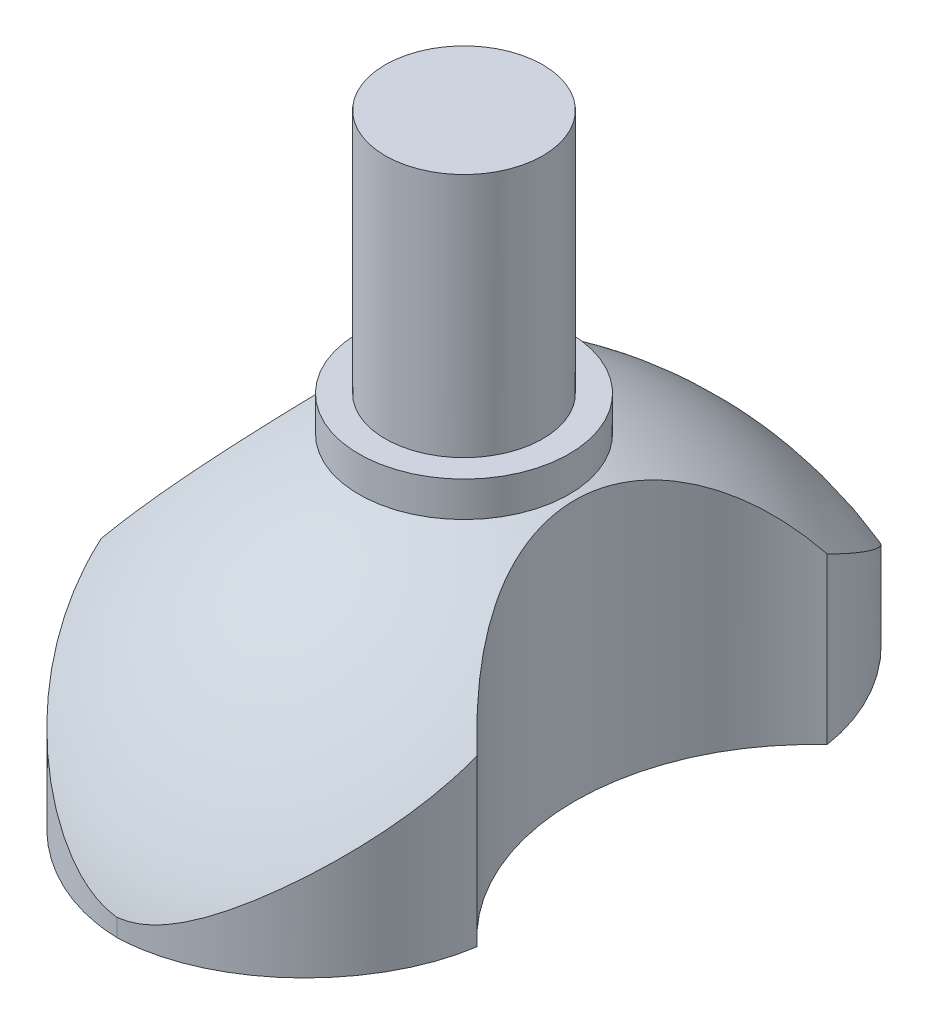
SolidWorks part; units mm, degrees
ref_plane "Front Plane" through (0, 0, 0) normal (0, 0, 1) x (1, 0, 0)
ref_plane "Top Plane" through (0, 0, 0) normal (0, 1, 0) x (1, 0, 0)
ref_plane "Right Plane" through (0, 0, 0) normal (1, 0, 0) x (0, 0, -1)
sketch "Sketch1" plane through (0, 0, 0) normal (0, 1, 0) x (1, 0, 0)
  circle A0 centre (0, 0) radius 5
  circle A1 centre (0, 0) radius 3
  dimension "D1" = 6
  dimension "D2" = 10
extrude "Boss-Extrude2" add sketch "Sketch1" along normal mid plane 35
sketch "Sketch4" plane through (0, 17.5, 0) normal (0, 1, 0) x (1, 0, 0)
  line L0 (3, 0) -> (21, 0)
  circle A0 centre (0, 0) radius 3 construction
  dimension "D1" = 18
extrude "Extrude-Thin1" add sketch "Sketch4" against normal blind 35 thin thin type mid plane wall 1
pattern_circular "CirPattern1" count 9 over 360 about axis through (0, 0, 0) along (0, 1, 0) of "Extrude-Thin1"
ref_plane "Plane1" through (0, -17.5, 0) normal (0, -1, 0) x (-1, 0, 0)
sketch "Sketch5" plane through (0, -17.5, 0) normal (0, -1, 0) x (-1, 0, 0)
  circle A0 centre (0, 0) radius 3
extrude "Boss-Extrude3" add sketch "Sketch5" against normal blind 15
sketch "Sketch6" plane through (0, -17.5, 0) normal (0, -1, 0) x (-1, 0, 0)
  circle A0 centre (0, 0) radius 3.5
  circle A1 centre (0, 0) radius 5
  circle A2 centre (0, 0) radius 1.5
  dimension "D1" = 1.5
  dimension "D2" = 10
  dimension "D3" = 2
extrude "Cut-Extrude1" cut sketch "Sketch6" against normal blind 6 contours A0 A2
sketch "Sketch15" plane through (0, -17.5, 0) normal (0, -1, 0) x (1, 0, 0)
  circle A0 centre (0, 0) radius 1.5
extrude "Cut-Extrude2" cut sketch "Sketch15" against normal blind 2
sketch "Sketch17" plane through (0, -17.5, 0) normal (0, -1, 0) x (1, 0, 0)
  line L0 (21, -0.5) -> (21, 0.5) construction
  circle A0 centre (18.5, 0) radius 2.5
  dimension "D1" = 5
  dimension "D2" = 2.5
extrude "Boss-Extrude4" add sketch "Sketch17" against normal blind 3
sketch "Sketch18" plane through (0, -17.5, 0) normal (0, -1, 0) x (1, 0, 0)
  circle A0 centre (18.5, 0) radius 2
  dimension "D1" = 4
extrude "Cut-Extrude3" cut sketch "Sketch18" against normal blind 2
sketch "Sketch19" plane through (0, 17.5, 0) normal (0, 1, 0) x (1, 0, 0)
  circle A0 centre (0, 0) radius 4
  circle A1 centre (0, 0) radius 3 construction
  dimension "D1" = 1
extrude "Cut-Extrude4" cut sketch "Sketch19" against normal up to surface (20 mm away) up to face at (0, -2.5, -3)
sketch "Sketch20" plane through (0, -17.5, 0) normal (0, -1, 0) x (-1, 0, 0)
  line L1 (22.8386, 22.8623) -> (-22.8386, 22.8623)
  line L2 (22.8386, 22.8623) -> (22.8386, -22.8623)
  line L3 (22.8386, -22.8623) -> (-22.8386, -22.8623)
  line L4 (-22.8386, 22.8623) -> (-22.8386, -22.8623)
  line L5 (22.8386, 22.8623) -> (-22.8386, -22.8623) construction
  line L6 (22.8386, -22.8623) -> (-22.8386, 22.8623) construction
  point P0 (0, 0)
extrude "Cut-Extrude5" cut sketch "Sketch20" against normal blind 8
sketch "Sketch21" plane through (0, -9.5, 0) normal (0, -1, 0) x (1, 0, 0)
  circle A0 centre (0, 0) radius 3
  dimension "D1" = 6
extrude "Boss-Extrude5" add sketch "Sketch21" along normal blind 1
sketch "Sketch22" plane through (0, 0, 0) normal (0, 0, 1) x (1, 0, 0)
  line L0 (0, 0) -> (0, -37.0893) construction
sketch "Sketch23" plane through (0, 0, 0) normal (1, 0, 0) x (0, 0, -1)
  line L0 (-8.7928, -17.5) -> (7.1377, -17.5) construction
  line L1 (-13.1155, -9.5) -> (-2.8148, -9.5) construction
  line L2 (-55, -17.5) -> (55, -17.5) construction
  line L3 (-3, -10.5) -> (-2, -10.5)
  line L4 (-3, -10.5) -> (3, -10.5) construction
  line L5 (-9.9121, -17.5) -> (-8.9121, -17.5)
  line L6 (0, -11.1307) -> (0, -16.3839) construction
  line L7 (0, 0) -> (0, -37.0893) construction
  line L8 (-8.9121, -17.5) -> (0, -17.5)
  line L9 (0, -17.5) -> (0, -10.5)
  line L10 (0, -10.5) -> (-2, -10.5)
  arc A0 (-3, -10.5) -> (-9.9121, -17.5) centre (0.7568, -21.1223) ccw
  dimension "D1" = 8
  dimension "D2" = 1
  dimension "D3" = 1
revolve "Revolve1" add sketch "Sketch23" angle 360 about L6
sketch "Sketch24" plane through (0, -17.5, 0) normal (0, -1, 0) x (1, 0, 0)
  circle A2 centre (0, 0) radius 9.9121
  circle A3 centre (0, 0) radius 9.9121
  dimension "D1" = 0
extrude "Boss-Extrude6" add sketch "Sketch24" along normal blind 0.5
sketch "Sketch25" plane through (0, -18, 0) normal (0, -1, 0) x (1, 0, 0)
  line L0 (-1.1163, 9.8491) -> (1.1163, -9.8491) construction
  circle A0 centre (0, 0) radius 9.9121 construction
  circle A1 centre (-0.5667, 5) radius 3.2
  point P6 (0, 0)
  dimension "D1" = 6.4
  dimension "D2" = 5
extrude "Cut-Extrude6" cut sketch "Sketch25" against normal blind 2.1
sketch "Sketch26" plane through (0, -18, 0) normal (0, -1, 0) x (1, 0, 0)
  circle A0 centre (-0.5667, 5) radius 3.2
extrude "Boss-Extrude7" add sketch "Sketch26" against normal blind 0.25
sketch "Sketch27" plane through (0, -18, 0) normal (0, -1, 0) x (1, 0, 0)
  line L0 (0, 9.9121) -> (0, -9.9121) construction
  line L1 (-9.9121, 0) -> (9.9121, 0) construction
  arc A1 (-7.6138, 6.3467) -> (-7.6138, -6.3467) centre (-9.9121, 0) cw
  circle A2 centre (0, 0) radius 9.9121 construction
  arc A3 (7.6138, 6.3467) -> (7.6138, -6.3467) centre (9.9121, 0) ccw
  arc A4 (7.6138, 6.3467) -> (7.6138, -6.3467) centre (0, 0) cw
  arc A5 (-7.6138, 6.3467) -> (-7.6138, -6.3467) centre (0, 0) ccw
  arc A6 (-7.6138, 6.3467) -> (0, 9.9121) centre (0, 0) cw
  arc A7 (7.6138, 6.3467) -> (0, 9.9121) centre (0, 0) ccw
  arc A8 (7.6138, -6.3467) -> (0, -9.9121) centre (0, 0) cw
  arc A9 (-7.6138, -6.3467) -> (0, -9.9121) centre (0, 0) ccw
  spline S0 degree 3 poles (-5.3686, 4.9919) (-4.9981, 7.5397) (-2.6164, 9.8379) (0, 9.9121) knots 0 0 0 0 1 1 1 1
  spline S1 degree 3 poles (5.3686, 4.9919) (4.9981, 7.5397) (2.6164, 9.8379) (0, 9.9121) knots 0 0 0 0 1 1 1 1
  spline S2 degree 3 poles (5.3686, -4.9919) (4.9981, -7.5397) (2.6164, -9.8379) (0, -9.9121) knots 0 0 0 0 1 1 1 1
  spline S3 degree 3 poles (-5.3686, -4.9919) (-4.9981, -7.5397) (-2.6164, -9.8379) (0, -9.9121) knots 0 0 0 0 1 1 1 1
  circle M1 centre (0, 0) radius 9.9121
extrude "Cut-Extrude8" cut sketch "Sketch27" against normal blind 7.5 contours A1 M1 | A3 M1 | S3 A1 M1 | A3 S2 M1 | A1 S0 M1 | S1 A3 M1
sketch "Sketch28" plane through (0, -18, 0) normal (0, -1, 0) x (1, 0, 0)
  circle A0 centre (0, 0) radius 0.5
  dimension "D1" = 1
extrude "Cut-Extrude9" cut sketch "Sketch28" against normal blind 1.5
sketch "Sketch29" plane through (0, 17.5, 0) normal (0, 1, 0) x (1, 0, 0)
  line L108 (3.4896, -3.5809) -> (15.7655, -13.8816)
  line L109 (15.7655, -13.8816) -> (16.4083, -13.1155)
  line L110 (16.4083, -13.1155) -> (4.1324, -2.8148)
  line L111 (4.9749, -0.5) -> (21, -0.5)
  line L112 (21, -0.5) -> (21, 0.5)
  line L113 (21, 0.5) -> (4.9749, 0.5)
  line L114 (4.1324, 2.8148) -> (16.4083, 13.1155)
  line L115 (16.4083, 13.1155) -> (15.7655, 13.8816)
  line L116 (15.7655, 13.8816) -> (3.4896, 3.5809)
  line L117 (1.3563, 4.8125) -> (4.139, 20.5941)
  line L118 (4.139, 20.5941) -> (3.1542, 20.7678)
  line L119 (3.1542, 20.7678) -> (0.3715, 4.9862)
  line L120 (-2.0545, 4.5584) -> (-10.067, 18.4365)
  line L121 (-10.067, 18.4365) -> (-10.933, 17.9365)
  line L122 (-10.933, 17.9365) -> (-2.9205, 4.0584)
  line L123 (-4.5039, 2.1714) -> (-19.5625, 7.6523)
  line L124 (-19.5625, 7.6523) -> (-19.9046, 6.7126)
  line L125 (-19.9046, 6.7126) -> (-4.8459, 1.2317)
  line L126 (-4.8459, -1.2317) -> (-19.9046, -6.7126)
  line L127 (-19.9046, -6.7126) -> (-19.5625, -7.6523)
  line L128 (-19.5625, -7.6523) -> (-4.5039, -2.1714)
  line L129 (-2.9205, -4.0584) -> (-10.933, -17.9365)
  line L130 (-10.933, -17.9365) -> (-10.067, -18.4365)
  line L131 (-10.067, -18.4365) -> (-2.0545, -4.5584)
  line L132 (0.3715, -4.9862) -> (3.1542, -20.7678)
  line L133 (3.1542, -20.7678) -> (4.139, -20.5941)
  line L134 (4.139, -20.5941) -> (1.3563, -4.8125)
  line L135 (3.4896, -3.5809) -> (15.7655, -13.8816)
  line L136 (15.7655, -13.8816) -> (16.4083, -13.1155)
  line L137 (16.4083, -13.1155) -> (4.1324, -2.8148)
  line L138 (4.9749, -0.5) -> (21, -0.5)
  line L139 (21, -0.5) -> (21, 0.5)
  line L140 (21, 0.5) -> (4.9749, 0.5)
  line L141 (4.1324, 2.8148) -> (16.4083, 13.1155)
  line L142 (16.4083, 13.1155) -> (15.7655, 13.8816)
  line L143 (15.7655, 13.8816) -> (3.4896, 3.5809)
  line L144 (1.3563, 4.8125) -> (4.139, 20.5941)
  line L145 (4.139, 20.5941) -> (3.1542, 20.7678)
  line L146 (3.1542, 20.7678) -> (0.3715, 4.9862)
  line L147 (-2.0545, 4.5584) -> (-10.067, 18.4365)
  line L148 (-10.067, 18.4365) -> (-10.933, 17.9365)
  line L149 (-10.933, 17.9365) -> (-2.9205, 4.0584)
  line L150 (-4.5039, 2.1714) -> (-19.5625, 7.6523)
  line L151 (-19.5625, 7.6523) -> (-19.9046, 6.7126)
  line L152 (-19.9046, 6.7126) -> (-4.8459, 1.2317)
  line L153 (-4.8459, -1.2317) -> (-19.9046, -6.7126)
  line L154 (-19.9046, -6.7126) -> (-19.5625, -7.6523)
  line L155 (-19.5625, -7.6523) -> (-4.5039, -2.1714)
  line L156 (-2.9205, -4.0584) -> (-10.933, -17.9365)
  line L157 (-10.933, -17.9365) -> (-10.067, -18.4365)
  line L158 (-10.067, -18.4365) -> (-2.0545, -4.5584)
  line L159 (0.3715, -4.9862) -> (3.1542, -20.7678)
  line L160 (3.1542, -20.7678) -> (4.139, -20.5941)
  line L161 (4.139, -20.5941) -> (1.3563, -4.8125)
  arc A36 (1.3563, -4.8125) -> (3.4896, -3.5809) centre (0, 0) ccw
  arc A37 (4.1324, -2.8148) -> (4.9749, -0.5) centre (0, 0) ccw
  arc A38 (4.9749, 0.5) -> (4.1324, 2.8148) centre (0, 0) ccw
  arc A39 (3.4896, 3.5809) -> (1.3563, 4.8125) centre (0, 0) ccw
  arc A40 (0.3715, 4.9862) -> (-2.0545, 4.5584) centre (0, 0) ccw
  arc A41 (-2.9205, 4.0584) -> (-4.5039, 2.1714) centre (0, 0) ccw
  arc A42 (-4.8459, 1.2317) -> (-4.8459, -1.2317) centre (0, 0) ccw
  arc A43 (-4.5039, -2.1714) -> (-2.9205, -4.0584) centre (0, 0) ccw
  arc A44 (-2.0545, -4.5584) -> (0.3715, -4.9862) centre (0, 0) ccw
  arc A45 (1.3563, -4.8125) -> (3.4896, -3.5809) centre (0, 0) ccw
  arc A46 (4.1324, -2.8148) -> (4.9749, -0.5) centre (0, 0) ccw
  arc A47 (4.9749, 0.5) -> (4.1324, 2.8148) centre (0, 0) ccw
  arc A48 (3.4896, 3.5809) -> (1.3563, 4.8125) centre (0, 0) ccw
  arc A49 (0.3715, 4.9862) -> (-2.0545, 4.5584) centre (0, 0) ccw
  arc A50 (-2.9205, 4.0584) -> (-4.5039, 2.1714) centre (0, 0) ccw
  arc A51 (-4.8459, 1.2317) -> (-4.8459, -1.2317) centre (0, 0) ccw
  arc A52 (-4.5039, -2.1714) -> (-2.9205, -4.0584) centre (0, 0) ccw
  arc A53 (-2.0545, -4.5584) -> (0.3715, -4.9862) centre (0, 0) ccw
  dimension "D1" = 0
extrude "Cut-Extrude10" cut sketch "Sketch29" against normal blind 7
sketch "Sketch30" plane through (0, -2.5, 0) normal (0, 1, 0) x (1, 0, 0)
  circle A1 centre (0, 0) radius 4
  circle A2 centre (0, 0) radius 4
  dimension "D1" = 0
extrude "Boss-Extrude8" add sketch "Sketch30" along normal blind 10
sketch "Sketch31" plane through (0, -9.5, 0) normal (0, -1, 0) x (1, 0, 0)
  line L54 (-2.0545, 4.5584) -> (-10.067, 18.4365)
  line L55 (-10.067, 18.4365) -> (-10.933, 17.9365)
  line L56 (-10.933, 17.9365) -> (-2.9205, 4.0584)
  line L57 (-4.5039, 2.1714) -> (-19.5625, 7.6523)
  line L58 (-19.5625, 7.6523) -> (-19.9046, 6.7126)
  line L59 (-19.9046, 6.7126) -> (-4.8459, 1.2317)
  line L60 (-4.8459, -1.2317) -> (-19.9046, -6.7126)
  line L61 (-19.9046, -6.7126) -> (-19.5625, -7.6523)
  line L62 (-19.5625, -7.6523) -> (-4.5039, -2.1714)
  line L63 (-2.9205, -4.0584) -> (-10.933, -17.9365)
  line L64 (-10.933, -17.9365) -> (-10.067, -18.4365)
  line L65 (-10.067, -18.4365) -> (-2.0545, -4.5584)
  line L66 (0.3715, -4.9862) -> (3.1542, -20.7678)
  line L67 (3.1542, -20.7678) -> (4.139, -20.5941)
  line L68 (4.139, -20.5941) -> (1.3563, -4.8125)
  line L69 (3.4896, -3.5809) -> (15.7655, -13.8816)
  line L70 (15.7655, -13.8816) -> (16.4083, -13.1155)
  line L71 (16.4083, -13.1155) -> (4.1324, -2.8148)
  line L72 (4.9749, -0.5) -> (21, -0.5)
  line L73 (21, -0.5) -> (21, 0.5)
  line L74 (21, 0.5) -> (4.9749, 0.5)
  line L75 (4.1324, 2.8148) -> (16.4083, 13.1155)
  line L76 (16.4083, 13.1155) -> (15.7655, 13.8816)
  line L77 (15.7655, 13.8816) -> (3.4896, 3.5809)
  line L78 (1.3563, 4.8125) -> (4.139, 20.5941)
  line L79 (4.139, 20.5941) -> (3.1542, 20.7678)
  line L80 (3.1542, 20.7678) -> (0.3715, 4.9862)
  line L81 (-2.0545, 4.5584) -> (-10.067, 18.4365)
  line L82 (-10.067, 18.4365) -> (-10.933, 17.9365)
  line L83 (-10.933, 17.9365) -> (-2.9205, 4.0584)
  line L84 (-4.5039, 2.1714) -> (-19.5625, 7.6523)
  line L85 (-19.5625, 7.6523) -> (-19.9046, 6.7126)
  line L86 (-19.9046, 6.7126) -> (-4.8459, 1.2317)
  line L87 (-4.8459, -1.2317) -> (-19.9046, -6.7126)
  line L88 (-19.9046, -6.7126) -> (-19.5625, -7.6523)
  line L89 (-19.5625, -7.6523) -> (-4.5039, -2.1714)
  line L90 (-2.9205, -4.0584) -> (-10.933, -17.9365)
  line L91 (-10.933, -17.9365) -> (-10.067, -18.4365)
  line L92 (-10.067, -18.4365) -> (-2.0545, -4.5584)
  line L93 (0.3715, -4.9862) -> (3.1542, -20.7678)
  line L94 (3.1542, -20.7678) -> (4.139, -20.5941)
  line L95 (4.139, -20.5941) -> (1.3563, -4.8125)
  line L96 (3.4896, -3.5809) -> (15.7655, -13.8816)
  line L97 (15.7655, -13.8816) -> (16.4083, -13.1155)
  line L98 (16.4083, -13.1155) -> (4.1324, -2.8148)
  line L99 (4.9749, -0.5) -> (21, -0.5)
  line L100 (21, -0.5) -> (21, 0.5)
  line L101 (21, 0.5) -> (4.9749, 0.5)
  line L102 (4.1324, 2.8148) -> (16.4083, 13.1155)
  line L103 (16.4083, 13.1155) -> (15.7655, 13.8816)
  line L104 (15.7655, 13.8816) -> (3.4896, 3.5809)
  line L105 (1.3563, 4.8125) -> (4.139, 20.5941)
  line L106 (4.139, 20.5941) -> (3.1542, 20.7678)
  line L107 (3.1542, 20.7678) -> (0.3715, 4.9862)
  circle A9 centre (0, 0) radius 2.25
  arc A18 (-2.9205, 4.0584) -> (-4.5039, 2.1714) centre (0, 0) ccw
  arc A19 (-4.8459, 1.2317) -> (-4.8459, -1.2317) centre (0, 0) ccw
  arc A20 (-4.5039, -2.1714) -> (-2.9205, -4.0584) centre (0, 0) ccw
  arc A21 (-2.0545, -4.5584) -> (0.3715, -4.9862) centre (0, 0) ccw
  arc A22 (1.3563, -4.8125) -> (3.4896, -3.5809) centre (0, 0) ccw
  arc A23 (4.1324, -2.8148) -> (4.9749, -0.5) centre (0, 0) ccw
  arc A24 (4.9749, 0.5) -> (4.1324, 2.8148) centre (0, 0) ccw
  arc A25 (3.4896, 3.5809) -> (1.3563, 4.8125) centre (0, 0) ccw
  arc A26 (0.3715, 4.9862) -> (-2.0545, 4.5584) centre (0, 0) ccw
  arc A27 (-2.9205, 4.0584) -> (-4.5039, 2.1714) centre (0, 0) ccw
  arc A28 (-4.8459, 1.2317) -> (-4.8459, -1.2317) centre (0, 0) ccw
  arc A29 (-4.5039, -2.1714) -> (-2.9205, -4.0584) centre (0, 0) ccw
  arc A30 (-2.0545, -4.5584) -> (0.3715, -4.9862) centre (0, 0) ccw
  arc A31 (1.3563, -4.8125) -> (3.4896, -3.5809) centre (0, 0) ccw
  arc A32 (4.1324, -2.8148) -> (4.9749, -0.5) centre (0, 0) ccw
  arc A33 (4.9749, 0.5) -> (4.1324, 2.8148) centre (0, 0) ccw
  arc A34 (3.4896, 3.5809) -> (1.3563, 4.8125) centre (0, 0) ccw
  arc A35 (0.3715, 4.9862) -> (-2.0545, 4.5584) centre (0, 0) ccw
  dimension "D2" = 4.5
  dimension "D1" = 0
extrude "Cut-Extrude12" cut sketch "Sketch31" against normal blind 20
sketch "Sketch32" plane through (0, 7.5, 0) normal (0, 1, 0) x (1, 0, 0)
  circle A2 centre (0, 0) radius 2.25
  circle A3 centre (0, 0) radius 2.25
  dimension "D1" = 0
extrude "Cut-Extrude13" cut sketch "Sketch32" against normal blind 10
equation "\"NumFlaps\"=9"
equation "\"D1@CirPattern1\"=\"NumFlaps\""
equation "\"FlapHeight\"=35"
equation "\"D1@Extrude-Thin1\"=\"FlapHeight\""
equation "\"FanBaseHeight\"=35"
equation "\"D1@Boss-Extrude2\"=\"FanBaseHeight\""
equation "\"FanExtrude\"=6"
equation "\"D1@Sketch1\"=\"FanExtrude\""
equation "\"magnet_diameter\"= 6.4"
equation "\"magnet_length\"= 2.1"
equation "\"magnet_distance\"= 5"
equation "\"D1@Sketch25\"=\"magnet_diameter\""
equation "\"D2@Sketch25\"=\"magnet_distance\""
equation "\"D1@Cut-Extrude6\"=\"magnet_length\""
equation "\"CutglobeArc\"=6.75"
equation "\"FanExtraExtrude\"=7"
equation "\"D1@Cut-Extrude10\"=\"FanExtraExtrude\""
